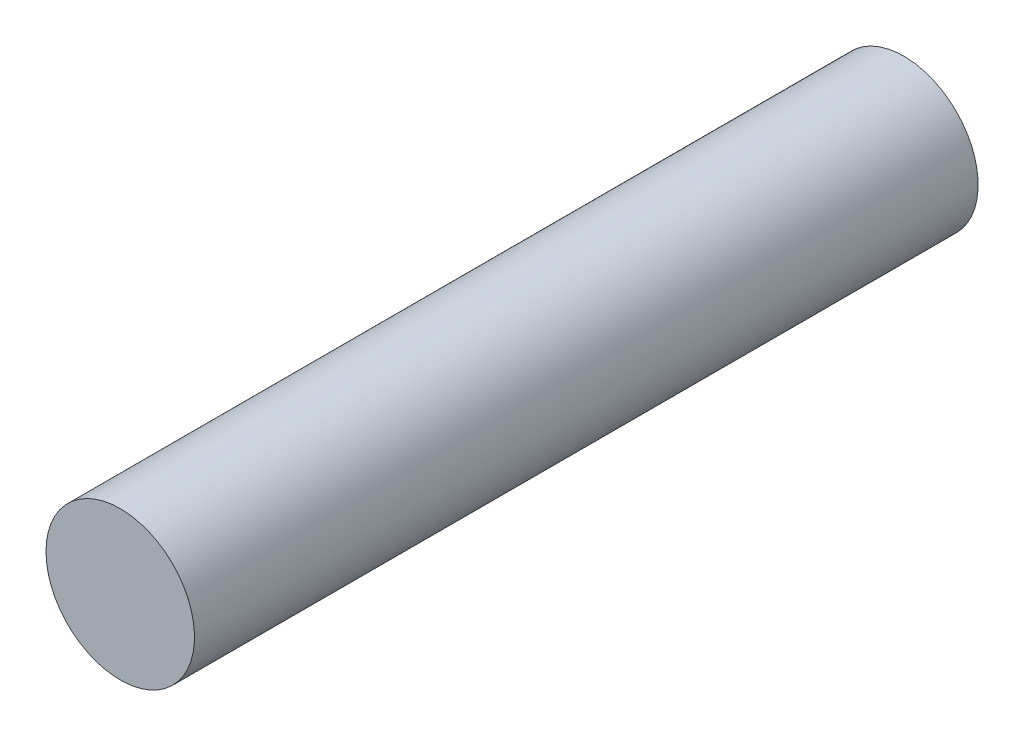
SolidWorks part; units mm, degrees
ref_plane "Front Plane" through (0, 0, 0) normal (0, 0, 1) x (1, 0, 0)
ref_plane "Top Plane" through (0, 0, 0) normal (0, 1, 0) x (1, 0, 0)
ref_plane "Right Plane" through (0, 0, 0) normal (1, 0, 0) x (0, 0, -1)
sketch "Sketch1" plane through (0, 0, 0) normal (0, 0, 1) x (1, 0, 0)
  circle A0 centre (0, 0) radius 90
  dimension "D1" = 180
extrude "Boss-Extrude1" add sketch "Sketch1" along normal blind 950
